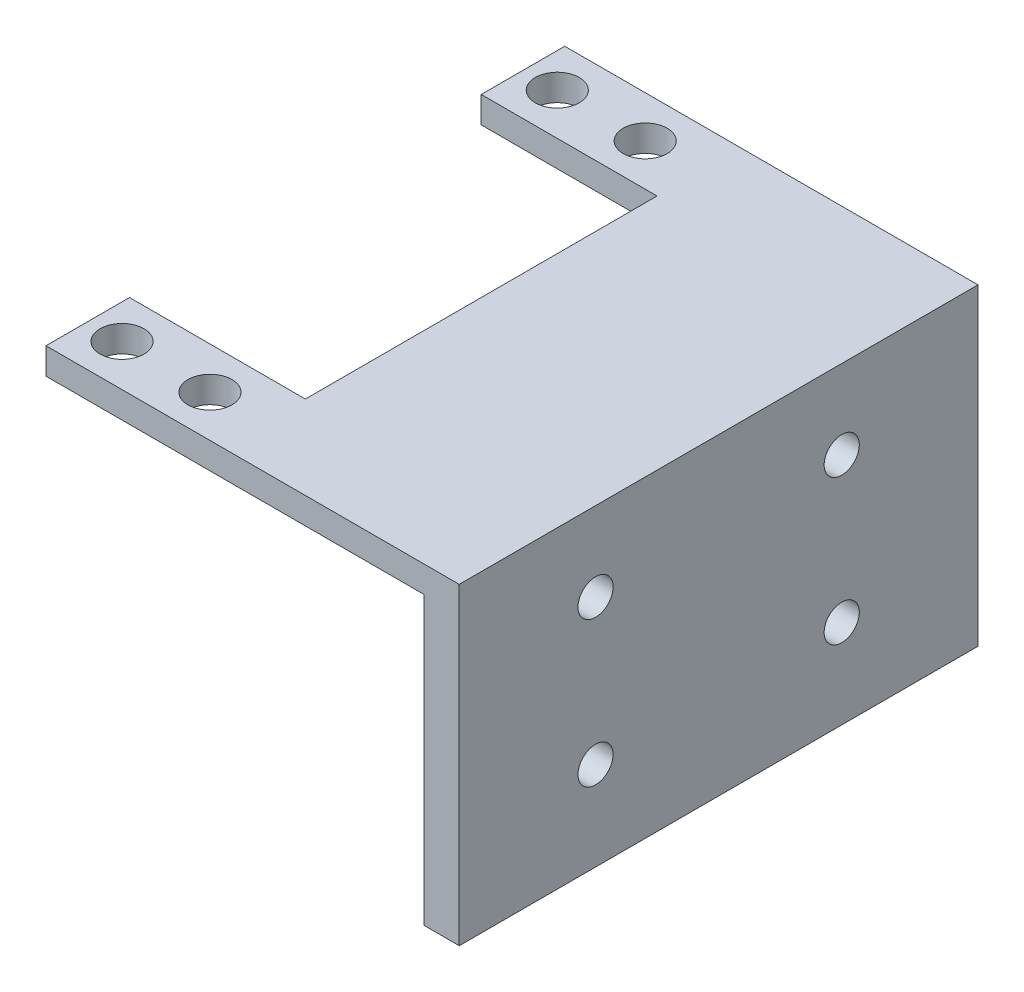
SolidWorks part; units mm, degrees
ref_plane "前视基准面" through (0, 0, 0) normal (0, 0, 1) x (1, 0, 0)
ref_plane "上视基准面" through (0, 0, 0) normal (0, 1, 0) x (1, 0, 0)
ref_plane "右视基准面" through (0, 0, 0) normal (1, 0, 0) x (0, 0, -1)
sketch "草图1" plane through (0, 0, 0) normal (0, 0, 1) x (1, 0, 0)
  line L1 (0, 0) -> (47, 0)
  line L2 (0, 0) -> (0, 35.6)
  line L3 (0, 35.6) -> (47, 35.6)
  line L4 (47, 0) -> (47, 35.6)
  dimension "D1" = 47
  dimension "D2" = 35.6
extrude "凸台-拉伸1" add sketch "草图1" along normal blind 59
sketch "草图3" plane through (0, 0, 0) normal (-1, 0, 0) x (0, 0, 1)
  line L0 (0, 35.6) -> (0, 0) construction
  line L3 (0, 32.6) -> (59, 32.6)
  line L4 (0, 32.6) -> (0, 0)
  line L5 (0, 0) -> (59, 0)
  line L6 (59, 32.6) -> (59, 0)
  dimension "D1" = 32.6
extrude "切除-拉伸1" cut sketch "草图3" against normal blind 43 contours L4 L3 L6 L5
sketch "草图4" plane through (0, 32.6, 0) normal (0, -1, 0) x (1, 0, 0)
  line L1 (0, 0) -> (0, 59) construction
  line L3 (0, 9.5) -> (20, 9.5)
  line L4 (0, 9.5) -> (0, 49.5)
  line L5 (0, 49.5) -> (20, 49.5)
  line L6 (20, 9.5) -> (20, 49.5)
  circle A0 centre (3.9, 54.25) radius 2.5
  circle A1 centre (13.9, 54.25) radius 2.5
  circle A2 centre (13.9, 4.75) radius 2.5
  circle A3 centre (3.9, 4.75) radius 2.5
  dimension "D1" = 10
  dimension "D2" = 3.9
  dimension "D3" = 10
  dimension "D4" = 3.9
  dimension "D5" = 20
extrude "切除-拉伸2" cut sketch "草图4" against normal blind 49
sketch "草图6" plane through (43, 0, 0) normal (-1, 0, 0) x (0, 0, 1)
  line L1 (9.5, 32.6) -> (49.5, 32.6) construction
  circle A4 centre (43.5, 26.6) radius 2
  circle A5 centre (15.5, 26.6) radius 2
  circle A7 centre (43.5, 10.1) radius 2
  circle A8 centre (15.5, 10.1) radius 2
  dimension "D1" = 6
  dimension "D2" = 6
  dimension "D3" = 16.5
  dimension "D4" = 16.5
  dimension "D5" = 28
extrude "切除-拉伸3" cut sketch "草图6" against normal blind 10
